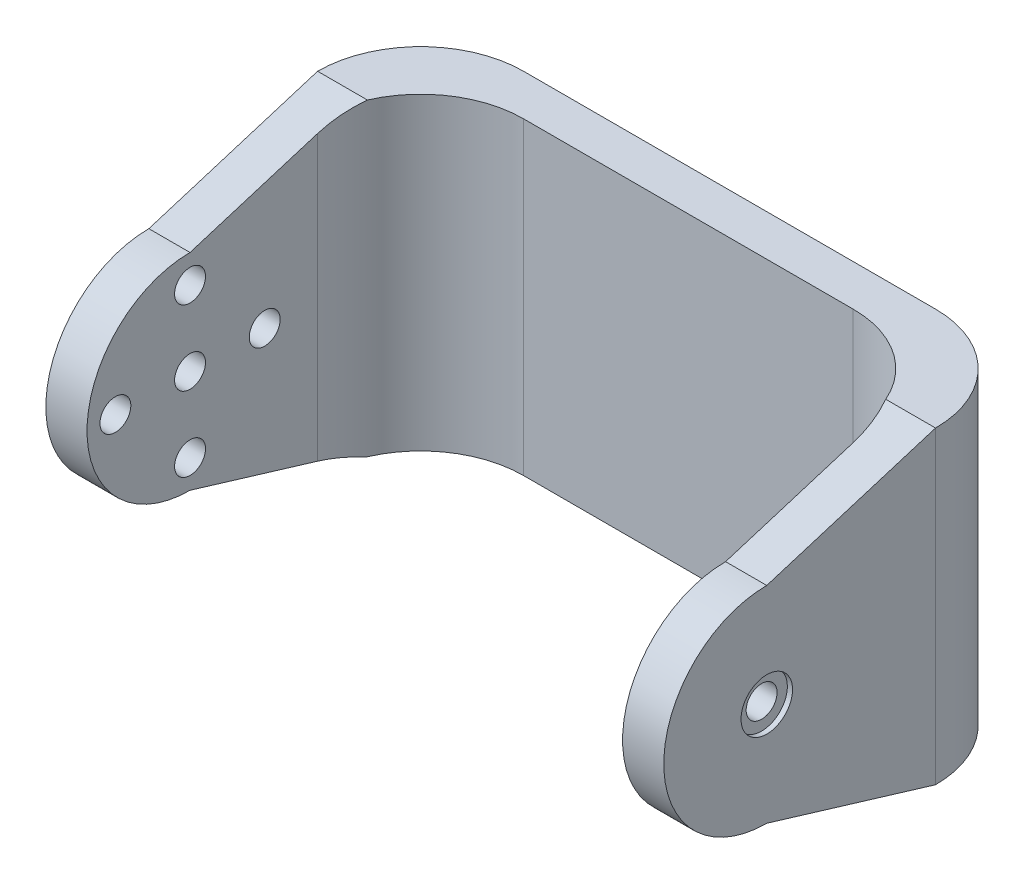
SolidWorks part; units mm, degrees
ref_plane "前视基准面" through (0, 0, 0) normal (0, 0, 1) x (1, 0, 0)
ref_plane "上视基准面" through (0, 0, 0) normal (0, 1, 0) x (1, 0, 0)
ref_plane "右视基准面" through (0, 0, 0) normal (1, 0, 0) x (0, 0, -1)
sketch "草图1" plane through (0, 0, 0) normal (0, 1, 0) x (1, 0, 0)
  line L1 (-28.3111, 18.1422) -> (23.6889, 18.1422)
  line L2 (-28.3111, 18.1422) -> (-28.3111, -16.8578)
  line L3 (-28.3111, -16.8578) -> (23.6889, -16.8578)
  line L4 (23.6889, 18.1422) -> (23.6889, -16.8578)
  line L5 (-28.3111, 18.1422) -> (-32.3111, 18.1422)
  line L6 (-28.3111, 18.1422) -> (-28.3111, -16.8578)
  line L7 (-28.3111, -16.8578) -> (-32.3111, -16.8578)
  line L8 (-32.3111, 18.1422) -> (-32.3111, -16.8578)
  line L9 (23.6889, 18.1422) -> (27.6889, 18.1422)
  line L10 (23.6889, 18.1422) -> (23.6889, -16.8578)
  line L11 (23.6889, -16.8578) -> (27.6889, -16.8578)
  line L12 (27.6889, 18.1422) -> (27.6889, -16.8578)
  line L13 (27.6889, 18.1422) -> (-32.3111, 18.1422)
  line L14 (27.6889, 18.1422) -> (27.6889, 22.1422)
  line L15 (27.6889, 22.1422) -> (-32.3111, 22.1422)
  line L16 (-32.3111, 18.1422) -> (-32.3111, 22.1422)
  dimension "D1" = 52
  dimension "D2" = 35
  dimension "D3" = 4
  dimension "D4" = 4
  dimension "D5" = 4
sketch "草图2" plane through (0, 0, 0) normal (0, 1, 0) x (1, 0, 0)
  line L0 (23.6889, -16.8578) -> (23.6889, 18.1422)
  line L1 (23.6889, 18.1422) -> (-28.3111, 18.1422)
  line L2 (-28.3111, 18.1422) -> (-28.3111, -16.8578)
  line L3 (-28.3111, -16.8578) -> (-32.3111, -16.8578)
  line L4 (-32.3111, -16.8578) -> (-32.3111, 22.1422)
  line L5 (-32.3111, 22.1422) -> (27.6889, 22.1422)
  line L6 (27.6889, 22.1422) -> (27.6889, -16.8578)
  line L7 (27.6889, -16.8578) -> (23.6889, -16.8578)
extrude "凸台-拉伸1" add sketch "草图2" along normal blind 30
fillet "圆角1" radius 10 2 edges at (27.6889, 15, -22.1422) (23.6889, 15, -18.1422)
fillet "圆角2" radius 10 2 edges at (-32.3111, 15, -22.1422) (-28.3111, 15, -18.1422)
ref_plane "基准面1" through (-32.3111, 0, 0) normal (-1, 0, 0) x (0, 0, 1)
sketch "草图3" plane through (-32.3111, 0, 0) normal (-1, 0, 0) x (0, 0, 1)
  circle A2 centre (4.2447, 14.9551) radius 10
  circle A7 centre (4.2447, 22.2051) radius 1.5
  circle A8 centre (11.4937, 14.9541) radius 1.5
  circle A9 centre (-3.0063, 14.9561) radius 1.5
  circle A10 centre (4.2447, 14.9551) radius 1.5
  circle A11 centre (4.2427, 7.7051) radius 1.5
sketch "草图4" plane through (-32.3111, 0, 0) normal (-1, 0, 0) x (0, 0, 1)
  circle A2 centre (-3.0063, 14.9561) radius 1.5
  circle A3 centre (-3.0063, 14.9561) radius 1.5
  circle A4 centre (11.4937, 14.9541) radius 1.5
  circle A5 centre (11.4937, 14.9541) radius 1.5
  circle A6 centre (4.2447, 22.2051) radius 1.5
  circle A7 centre (4.2447, 22.2051) radius 1.5
  circle A10 centre (4.2427, 7.7051) radius 1.5
  circle A11 centre (4.2427, 7.7051) radius 1.5
  circle A12 centre (4.2447, 14.9551) radius 1.5
  circle A13 centre (4.2447, 14.9551) radius 1.5
  dimension "D1" = 0
  dimension "D2" = 0
  dimension "D3" = 0
  dimension "D5" = 0
  dimension "D6" = 0
extrude "切除-拉伸1" cut sketch "草图4" against normal up to surface (4 mm away) up to face at (-28.3111, 15, 4.3578)
sketch "草图5" plane through (-32.3111, 0, 0) normal (-1, 0, 0) x (0, 0, 1)
  line L0 (16.8578, 0) -> (4.2447, 0)
  line L2 (-18.1422, 0) -> (16.8578, 0) construction
  line L3 (16.8578, 0) -> (16.8578, 30)
  line L4 (16.8578, 30) -> (4.2447, 30)
  line L5 (-12.1422, 30) -> (16.8578, 30) construction
  line L7 (-12.1422, 30) -> (4.2447, 24.9551)
  line L8 (-12.1422, 30) -> (4.2447, 30)
  line L9 (-12.1422, 0) -> (4.2447, 4.9551)
  line L10 (-12.1422, 0) -> (4.2447, 0)
  circle A0 centre (4.2447, 14.9551) radius 10 construction
  arc A1 (4.2447, 4.9551) -> (4.2447, 24.9551) centre (4.2447, 14.9551) ccw
extrude "切除-拉伸2" cut sketch "草图5" against normal through all
ref_plane "基准面2" through (27.6889, 0, 0) normal (1, 0, 0) x (0, 0, -1)
sketch "草图6" plane through (27.6889, 0, 0) normal (1, 0, 0) x (0, 0, -1)
  circle A0 centre (-4.2447, 14.9551) radius 1.5 construction
  circle A1 centre (-4.2447, 14.9551) radius 1.5
extrude "切除-拉伸3" cut sketch "草图6" against normal up to surface (4 mm away) up to face at (23.6889, 14.972, 0.5512)
sketch "草图7" plane through (27.6889, 0, 0) normal (1, 0, 0) x (0, 0, -1)
  circle A0 centre (-4.2447, 14.9551) radius 2.5
extrude "切除-拉伸4" cut sketch "草图7" against normal blind 0.5
